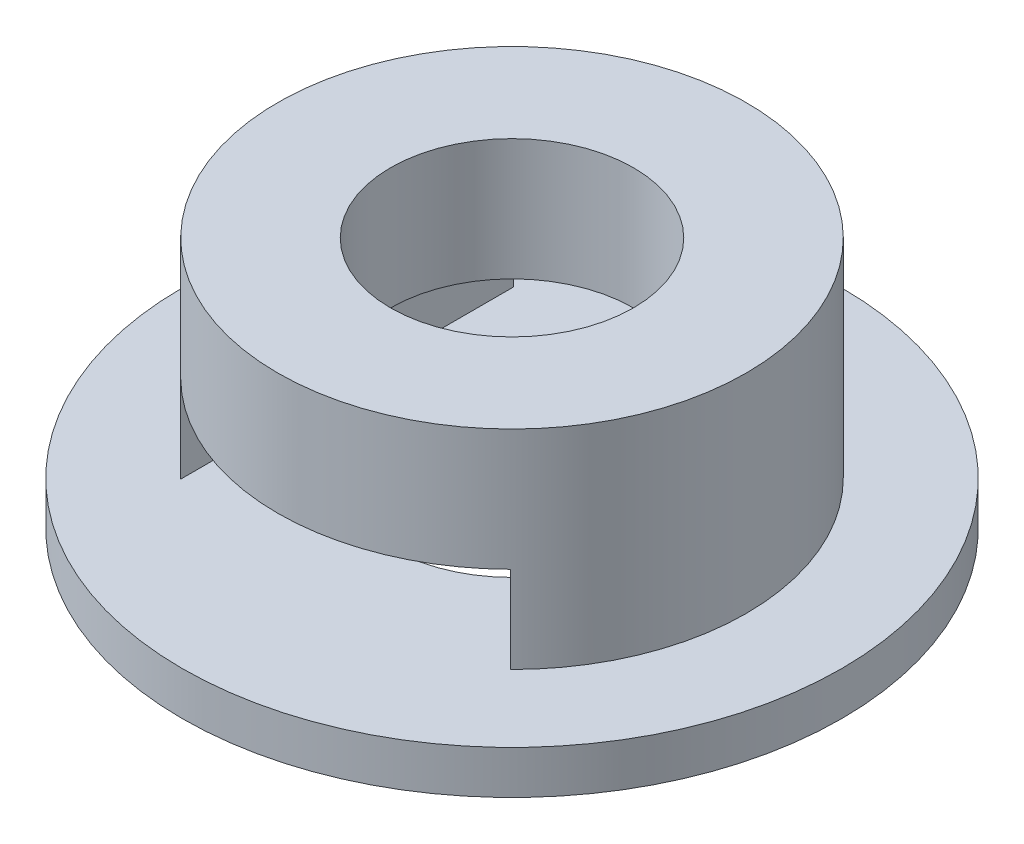
SolidWorks part; units mm, degrees
ref_plane "Front Plane" through (0, 0, 0) normal (0, 0, 1) x (1, 0, 0)
ref_plane "Top Plane" through (0, 0, 0) normal (0, 1, 0) x (1, 0, 0)
ref_plane "Right Plane" through (0, 0, 0) normal (1, 0, 0) x (0, 0, -1)
sketch "Sketch1" plane through (0, 0, 0) normal (0, 1, 0) x (1, 0, 0)
  circle A0 centre (0, 0) radius 19
extrude "Boss-Extrude1" add sketch "Sketch1" along normal blind 2.5
sketch "Sketch2" plane through (0, 2.5, 0) normal (0, 1, 0) x (1, 0, 0)
  circle A0 centre (0, 0) radius 13.5
extrude "Boss-Extrude2" add sketch "Sketch2" along normal blind 12
sketch "Sketch3" plane through (0, 14.5, 0) normal (0, 1, 0) x (1, 0, 0)
  circle A0 centre (0, 0) radius 7
extrude "Cut-Extrude1" cut sketch "Sketch3" against normal through all
sketch "Sketch4" plane through (0, 0, 0) normal (0, 0, 1) x (1, 0, 0)
  line L1 (-9.5, 2.5) -> (9.5, 2.5)
  line L2 (-9.5, 2.5) -> (-9.5, 7.5)
  line L3 (-9.5, 7.5) -> (9.5, 7.5)
  line L4 (9.5, 2.5) -> (9.5, 7.5)
  line L5 (-13.5, 17.5) -> (-13.5, 23.8432) construction
  line L6 (19, 2.5) -> (-19, 2.5) construction
  line L7 (13.5, 17.5) -> (13.5, 24.041) construction
  dimension "D1" = 4
  dimension "D2" = 4
extrude "Cut-Extrude2" cut sketch "Sketch4" against normal mid plane 35
